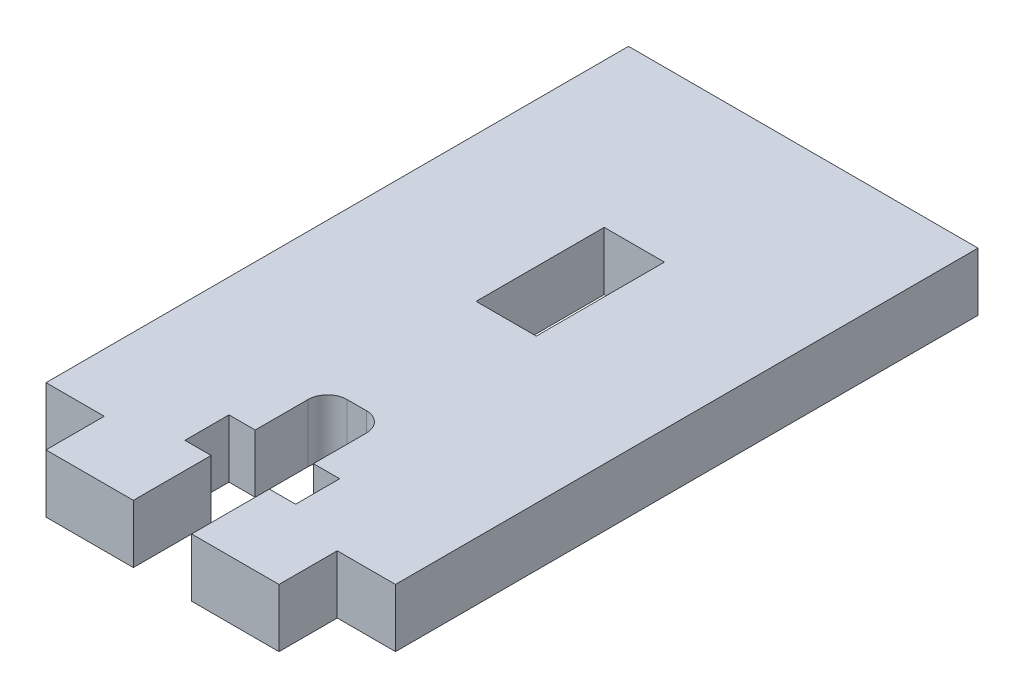
SolidWorks part; units mm, degrees
ref_plane "Plano frontal" through (0, 0, 0) normal (0, 0, 1) x (1, 0, 0)
ref_plane "Plano superior" through (0, 0, 0) normal (0, 1, 0) x (1, 0, 0)
ref_plane "Plano direito" through (0, 0, 0) normal (1, 0, 0) x (0, 0, -1)
sketch "Sketch1" plane through (0, 0, 0) normal (0, 1, 0) x (1, 0, 0)
  line L1 (-9, 15) -> (9, 15)
  line L2 (-9, 15) -> (-9, -15)
  line L3 (-9, -15) -> (9, -15)
  line L4 (9, 15) -> (9, -15)
  point P4 (0, 15)
  point P6 (-9, 0)
  dimension "D1" = 18
  dimension "D2" = 30
extrude "Boss-Extrude1" add sketch "Sketch1" along normal mid plane 3
sketch "Sketch2" plane through (0, 0, 0) normal (0, 1, 0) x (1, 0, 0)
  line L0 (-9, -15) -> (9, -15) construction
  line L1 (-6, -15) -> (6, -15)
  line L2 (-6, -15) -> (-6, -18)
  line L3 (-6, -18) -> (6, -18)
  line L4 (6, -15) -> (6, -18)
  line L5 (-9, 15) -> (-9, -15) construction
  line L6 (9, -15) -> (9, 15) construction
  point P6 (0, -15)
  dimension "D1" = 3
  dimension "D2" = 3
  dimension "D3" = 12
  dimension "D4" = 3
extrude "Boss-Extrude2" add sketch "Sketch2" along normal mid plane 3
sketch "Sketch4" plane through (0, 0, 0) normal (0, 1, 0) x (1, 0, 0)
  line L0 (-6, -18) -> (6, -18) construction
  line L1 (-1.5, -18) -> (1.5, -18)
  line L2 (-1.5, -18) -> (-1.5, -13.9961)
  line L3 (-0.5, -8) -> (0.5, -8)
  line L4 (1.5, -18) -> (1.5, -13.9961)
  line L5 (-6, -15) -> (-6, -18) construction
  line L6 (6, -18) -> (6, -15) construction
  line L7 (1.5, -11.7261) -> (2.85, -11.7261)
  line L8 (-2.85, -11.7261) -> (-1.5, -11.7261)
  line L9 (-2.85, -11.7261) -> (-2.85, -13.9961)
  line L10 (-2.85, -13.9961) -> (-1.5, -13.9961)
  line L11 (2.85, -11.7261) -> (2.85, -13.9961)
  line L12 (-1.5, -11.7261) -> (-1.5, -9)
  line L13 (1.5, -13.9961) -> (2.85, -13.9961)
  line L14 (1.5, -11.7261) -> (1.5, -9)
  arc A0 (0.5, -8) -> (1.5, -9) centre (0.5, -9) cw
  arc A1 (-1.5, -9) -> (-0.5, -8) centre (-0.5, -9) cw
  point P16 (1.5, -8)
  point P19 (-1.5, -8)
  dimension "D9" = 1
  dimension "D1" = 10
  dimension "D2" = 3
  dimension "D3" = 4.5
  dimension "D4" = 4.5
  dimension "D5" = 1.35
  dimension "D6" = 1.35
  dimension "D7" = 2.27
  dimension "D8" = 4.0039
extrude "Cut-Extrude2" cut sketch "Sketch4" against normal through all both and the other way through all
sketch "Sketch3" plane through (0, 0, 0) normal (0, 1, 0) x (1, 0, 0)
  line L0 (-9, -15) -> (-6, -15) construction
  line L1 (-5, 8) -> (5, 8) construction
  line L2 (-5, 8) -> (-5, -2) construction
  line L3 (-5, -2) -> (5, -2) construction
  line L4 (5, 8) -> (5, -2) construction
  line L5 (-1.55, 6.3) -> (1.55, 6.3)
  line L6 (-1.25, 6) -> (1.25, 6) construction
  line L7 (-1.25, 6) -> (-1.25, 0) construction
  line L8 (-1.25, 0) -> (1.25, 0) construction
  line L9 (1.25, 6) -> (1.25, 0) construction
  line L10 (1.55, 6.3) -> (1.55, -0.3)
  line L11 (-1.55, -0.3) -> (1.55, -0.3)
  line L12 (-1.55, 6.3) -> (-1.55, -0.3)
  point P4 (-5, 3)
  point P7 (0, -2)
  point P13 (-1.25, 3)
  point P14 (0, 0)
  dimension "D1" = 18
  dimension "D2" = 10
  dimension "D3" = 10
  dimension "D4" = 6
  dimension "D5" = 2.5
  dimension "D6" = 0.3
extrude "Cut-Extrude1" cut sketch "Sketch3" against normal through all both and the other way through all
